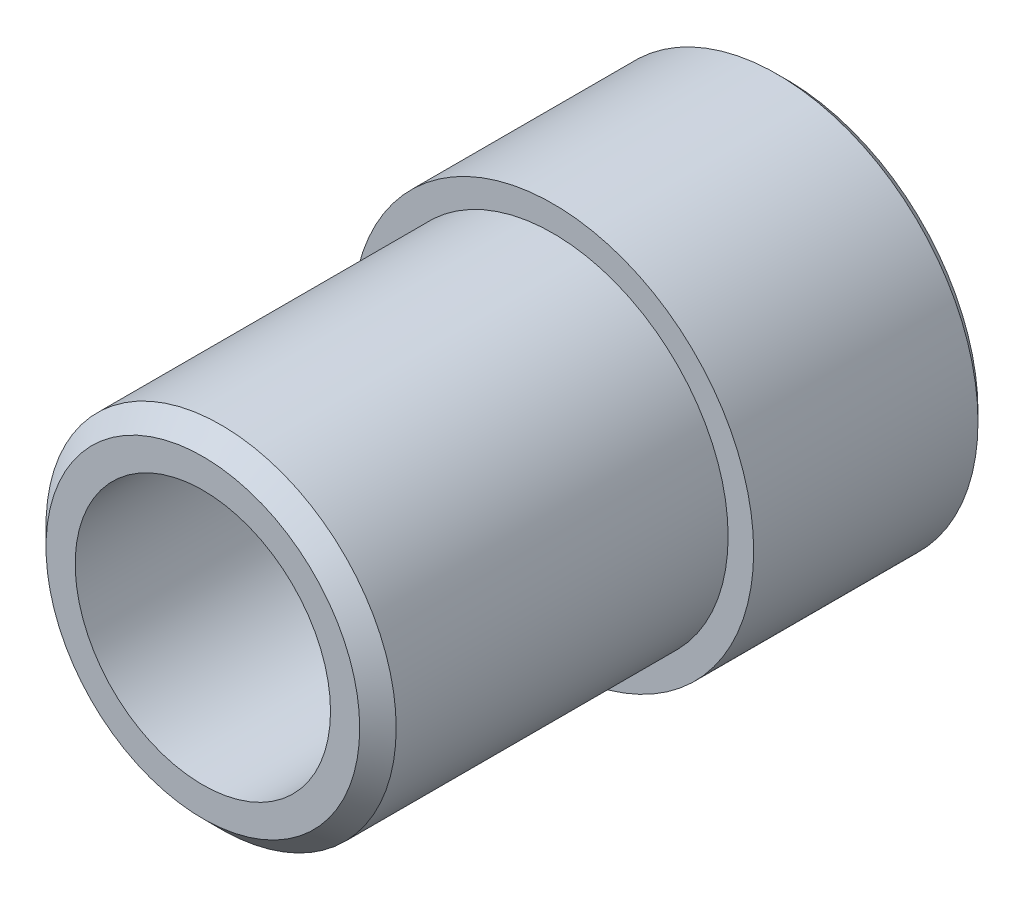
SolidWorks part; units mm, degrees
ref_plane "정면" through (0, 0, 0) normal (0, 0, 1) x (1, 0, 0)
ref_plane "윗면" through (0, 0, 0) normal (0, 1, 0) x (1, 0, 0)
ref_plane "우측면" through (0, 0, 0) normal (1, 0, 0) x (0, 0, -1)
sketch "스케치1" plane through (0, 0, 0) normal (0, 0, 1) x (1, 0, 0)
  circle A0 centre (0, 0) radius 8.4
  circle A1 centre (0, 0) radius 11
  dimension "D1" = 16.8
  dimension "D2" = 22
extrude "보스-돌출1" add sketch "스케치1" along normal blind 2
sketch "스케치2" plane through (0, 0, 2) normal (0, 0, 1) x (1, 0, 0)
  circle A0 centre (0, 0) radius 7
  circle A1 centre (0, 0) radius 9.6
  dimension "D1" = 19.2
  dimension "D2" = 14
extrude "보스-돌출2" add sketch "스케치2" along normal blind 30
chamfer "모따기1" distance 0.5 angle 45 1 edges at (8.4, 0, 0)
sketch "스케치3" plane through (0, 0, 2) normal (0, 0, 1) x (1, 0, 0)
  circle A0 centre (0, 0) radius 9.6
  circle A1 centre (0, 0) radius 11
  circle A2 centre (0, 0) radius 11 construction
  circle A3 centre (0, 0) radius 9.6 construction
extrude "보스-돌출3" add sketch "스케치3" along normal blind 10.8
chamfer "모따기2" distance 1 angle 45 1 edges at (9.6, 0, 32)
chamfer "모따기3" distance 0.3 angle 45 1 edges at (8.4, 0, 2)
chamfer "모따기4" distance 0.5 angle 45 1 edges at (11, 0, 0)
